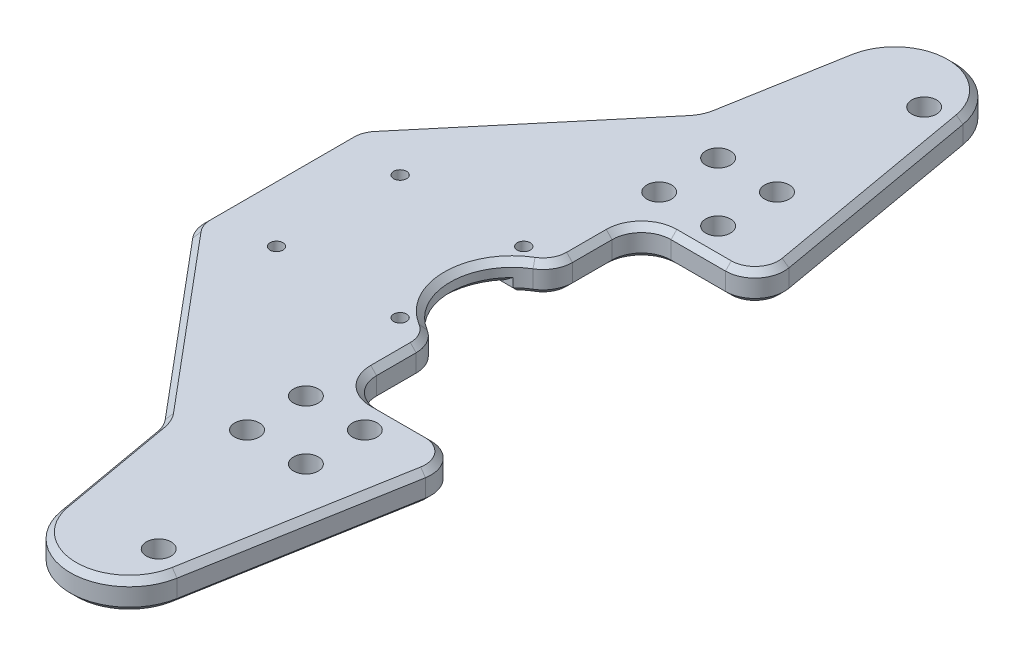
SolidWorks part; units mm, degrees
ref_plane "前视基准面" through (0, 0, 0) normal (0, 0, 1) x (1, 0, 0)
ref_plane "上视基准面" through (0, 0, 0) normal (0, 1, 0) x (1, 0, 0)
ref_plane "右视基准面" through (0, 0, 0) normal (1, 0, 0) x (0, 0, -1)
other "Configuration Table"
sketch "草图1" plane through (0, 0, 0) normal (0, 1, 0) x (1, 0, 0)
  line L0 (0, -25) -> (95.6592, -25) construction
  line L1 (0, -25) -> (0, -65) construction
  line L4 (16.1726, -30.8682) -> (9.8481, -66.7365)
  line L5 (-13.3665, -46.7828) -> (-9.8481, -66.7365)
  line L6 (11.2486, -25) -> (2, -25)
  line L7 (0, 0) -> (95.6592, 0) construction
  line L8 (0, 25) -> (0, 65) construction
  line L9 (11.2486, 25) -> (2, 25)
  line L10 (-13.3665, 46.7828) -> (-9.8481, 66.7365)
  line L11 (16.1726, 30.8682) -> (9.8481, 66.7365)
  line L12 (-14.4603, -44.4371) -> (-38.8302, -15.3941)
  line L13 (-40, -12.1801) -> (-40, 12.1801)
  line L14 (-38.8302, 15.3941) -> (-14.4603, 44.4371)
  line L15 (-3, 20) -> (-3, 13.2759)
  line L16 (-3, -13.2759) -> (-3, -20)
  arc A1 (-9.8481, -66.7365) -> (9.8481, -66.7365) centre (0, -65) ccw
  arc A4 (16.1726, -30.8682) -> (11.2486, -25) centre (11.2486, -30) ccw
  arc A7 (16.1726, 30.8682) -> (11.2486, 25) centre (11.2486, 30) cw
  arc A8 (-9.8481, 66.7365) -> (9.8481, 66.7365) centre (0, 65) cw
  arc A9 (-5.4194, 8.9934) -> (-5.4194, -8.9934) centre (0, 0) ccw
  arc A10 (-5.4194, 8.9934) -> (-3, 13.2759) centre (-8, 13.2759) ccw
  arc A11 (-3, -13.2759) -> (-5.4194, -8.9934) centre (-8, -13.2759) ccw
  arc A12 (2, -25) -> (-3, -20) centre (2, -20) cw
  arc A13 (-3, 20) -> (2, 25) centre (2, 20) cw
  arc A14 (-14.4603, 44.4371) -> (-13.3665, 46.7828) centre (-18.2905, 47.651) ccw
  arc A15 (-14.4603, -44.4371) -> (-13.3665, -46.7828) centre (-18.2905, -47.651) cw
  arc A16 (-38.8302, -15.3941) -> (-40, -12.1801) centre (-35, -12.1801) cw
  arc A17 (-40, 12.1801) -> (-38.8302, 15.3941) centre (-35, 12.1801) cw
  point P6 (17.2073, -25)
  point P25 (17.2073, 25)
  point P44 (-40, -14)
  point P47 (-40, 14)
  dimension "D2" = 10
  dimension "D3" = 80
  dimension "D4" = 5
  dimension "D8" = 21
  dimension "D12" = 5
  dimension "D5" = 50
  dimension "D6" = 3
  dimension "D7" = 28
  dimension "D9" = 40
  dimension "D10" = 50
  dimension "D11" = 65
extrude "凸台-拉伸1" add sketch "草图1" along normal mid plane 5
sketch "草图2" plane through (0, 2.5, 0) normal (0, 1, 0) x (1, 0, 0)
  line L0 (0, 0) -> (70.816, 0) construction
  line L1 (0, -65) -> (0, 65) construction
  line L2 (5, -65) -> (0, -65) construction
  circle A1 centre (5, -65) radius 2.1
  circle A2 centre (5, 65) radius 2.1
  dimension "D1" = 4.2
  dimension "D2" = 5
extrude "切除-拉伸1" cut sketch "草图2" against normal through all
sketch "草图3" plane through (0, -2.5, 0) normal (0, -1, 0) x (1, 0, 0)
  line L1 (0, 0) -> (-61.6695, 0) construction
  line L6 (-29.5, 10.5) -> (-8.5, 10.5) construction
  line L7 (-29.5, -10.5) -> (-8.5, -10.5) construction
  circle A2 centre (-8.5, 10.5) radius 1.1
  circle A3 centre (-29.5, 10.5) radius 1.1
  circle A6 centre (-29.5, -10.5) radius 1.1
  circle A7 centre (-8.5, -10.5) radius 1.1
  point P8 (0, 0)
  dimension "D3" = 21
  dimension "D1" = 2.2
  dimension "D2" = 8.5
  dimension "D4" = 21
extrude "切除-拉伸2" cut sketch "草图3" against normal through all
sketch "草图6" plane through (0, -2.5, 0) normal (0, -1, 0) x (1, 0, 0)
  line L0 (0, 0) -> (-48.2013, 0) construction
  line L2 (-36, -7.5) -> (0, -7.5)
  line L3 (-36, -7.5) -> (-36, 7.5)
  line L4 (-36, 7.5) -> (0, 7.5)
  line L5 (0, -7.5) -> (0, 7.5)
  line L6 (-36, -7.5) -> (0, 7.5) construction
  line L7 (-36, 7.5) -> (0, -7.5) construction
  point P3 (-18, 0)
  dimension "D1" = 15
  dimension "D2" = 36
extrude "切除-拉伸3" cut sketch "草图6" against normal blind 1.5
chamfer "倒角1" distance 1 angle 45 53 edges at (-11.6073, 2.5, 56.7596) (0, 2.5, 75) (13.0103, 2.5, 48.8024) (-11.6073, -2.5, 56.7596) (0, -2.5, 75) (13.0103, -2.5, 48.8024) (6.6243, 2.5, 25) (15.0788, 2.5, 26.7861) (15.0788, -2.5, 26.7861) (6.6243, -2.5, 25) (-11.6073, -2.5, -56.7596) (-13.759, -2.5, -45.5379) (0, -2.5, -75) (-26.6452, -2.5, -29.9156) (13.0103, -2.5, -48.8024) (-39.6985, -2.5, -13.8902) (15.0788, -2.5, -26.7861) (-40, -2.5, 0) (6.6243, -2.5, -25) (-39.6985, -2.5, 13.8902) (-1.5355, -2.5, -23.5355) (-26.6452, -2.5, 29.9156) (-3, -2.5, -16.638) (-13.759, -2.5, 45.5379) (-3.6467, -2.5, -10.8166) (-6.4274, -2.5, -8.3029) (-6.4274, -2.5, 8.3029) (-3.6467, -2.5, 10.8166) (-3, -2.5, 16.638) (-1.5355, -2.5, 23.5355) (13.0103, 2.5, -48.8024) (0, 2.5, -75) (15.0788, 2.5, -26.7861) (-11.6073, 2.5, -56.7596) (6.6243, 2.5, -25) (-13.759, 2.5, -45.5379) (-1.5355, 2.5, -23.5355) (-26.6452, 2.5, -29.9156) (-3, 2.5, -16.638) (-39.6985, 2.5, -13.8902) (-3.6467, 2.5, -10.8166) (-40, 2.5, 0) (-10.5, 2.5, 0) (-39.6985, 2.5, 13.8902) (-3.6467, 2.5, 10.8166) (-26.6452, 2.5, 29.9156) (-3, 2.5, 16.638) (-13.759, 2.5, 45.5379) (-1.5355, 2.5, 23.5355) (-10.5, -1, 0) (-21.6742, -2.5, -7.5) (-21.6742, -2.5, 7.5) (-36, -2.5, 0)
sketch "草图7" plane through (0, 2.5, 0) normal (0, 1, 0) x (1, 0, 0)
  line L0 (0, 0) -> (79.0215, 0) construction
  line L1 (0, -65) -> (0, 65) construction
  line L2 (-5, 30) -> (5, 30) construction
  line L3 (-5, -30) -> (5, -30) construction
  circle A0 centre (-5, 40) radius 2.1
  circle A1 centre (5, 40) radius 2.1
  circle A2 centre (5, -40) radius 2.1
  circle A3 centre (-5, -40) radius 2.1
  circle A4 centre (-5, 30) radius 2.1
  circle A5 centre (5, 30) radius 2.1
  circle A6 centre (5, -30) radius 2.1
  circle A7 centre (-5, -30) radius 2.1
  dimension "D1" = 4.2
  dimension "D2" = 10
  dimension "D3" = 40
  dimension "D4" = 4.2
  dimension "D5" = 10
  dimension "D6" = 10
extrude "切除-拉伸4" cut sketch "草图7" against normal through all both
